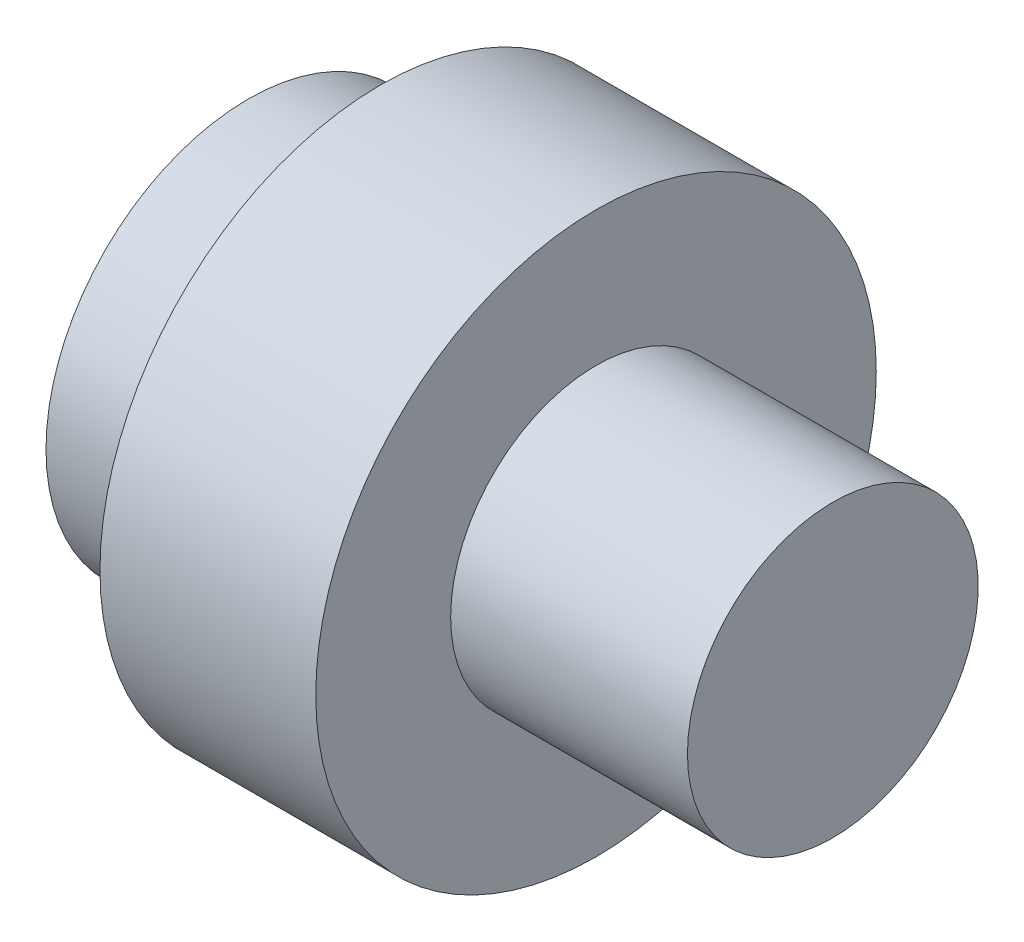
SolidWorks part; units mm, degrees
ref_plane "정면" through (0, 0, 0) normal (0, 0, 1) x (1, 0, 0)
ref_plane "윗면" through (0, 0, 0) normal (0, 1, 0) x (1, 0, 0)
ref_plane "우측면" through (0, 0, 0) normal (1, 0, 0) x (0, 0, -1)
sketch "스케치1" plane through (0, 0, 0) normal (0, 0, 1) x (1, 0, 0)
  line L0 (0, 0) -> (52.2313, 0) construction
  line L1 (0, 0) -> (0, 18.0801)
  line L2 (0, 18.0801) -> (11.7855, 18.0801)
  line L3 (11.7855, 18.0801) -> (11.7855, 25.0443)
  line L4 (11.7855, 25.0443) -> (31.071, 25.0443)
  line L5 (31.071, 25.0443) -> (31.071, 12.9909)
  line L6 (31.071, 12.9909) -> (52.2313, 12.9909)
  line L7 (52.2313, 12.9909) -> (52.2313, 0)
  line L8 (0, 0) -> (52.2313, 0)
revolve "회전1" add sketch "스케치1" angle 360 about L0
